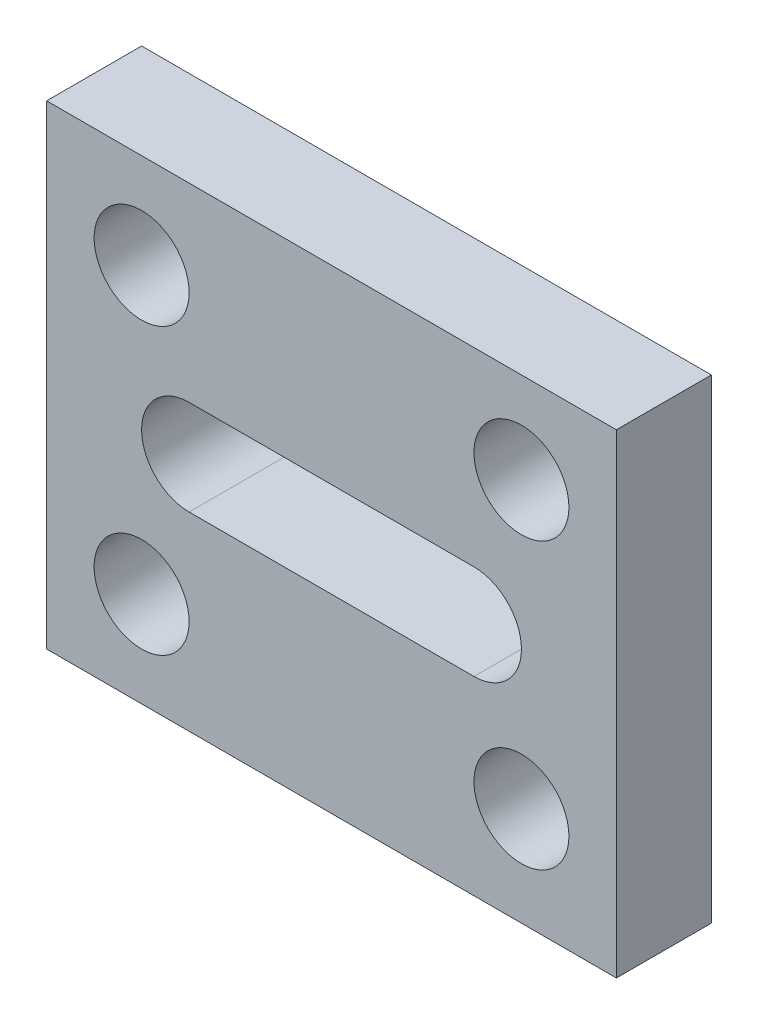
SolidWorks part; units mm, degrees
ref_plane "Front Plane" through (0, 0, 0) normal (0, 0, 1) x (1, 0, 0)
ref_plane "Top Plane" through (0, 0, 0) normal (0, 1, 0) x (1, 0, 0)
ref_plane "Right Plane" through (0, 0, 0) normal (1, 0, 0) x (0, 0, -1)
sketch "Sketch1" plane through (0, 0, 0) normal (0, 0, 1) x (1, 0, 0)
  line L1 (60, -50) -> (-60, -50)
  line L2 (60, -50) -> (60, 50)
  line L3 (60, 50) -> (-60, 50)
  line L4 (-60, -50) -> (-60, 50)
  line L5 (30, -10) -> (-30, -10)
  line L7 (30, 10) -> (-30, 10)
  arc A0 (-30, 10) -> (-30, -10) centre (-30, 0) ccw
  arc A1 (30, -10) -> (30, 10) centre (30, 0) ccw
  circle A2 centre (-40, -30) radius 10
  circle A3 centre (-40, 30) radius 10
  circle A4 centre (40, 30.8503) radius 10
  circle A5 centre (40, -29.1497) radius 10
  point P0 (0, 0)
  point P6 (0, 0)
  dimension "D9" = 20
  dimension "D10" = 20
  dimension "D11" = 20
  dimension "D8" = 20
  dimension "D1" = 100
  dimension "D2" = 120
  dimension "D3" = 60
  dimension "D4" = 20
extrude "Boss-Extrude1" add sketch "Sketch1" along normal blind 20
